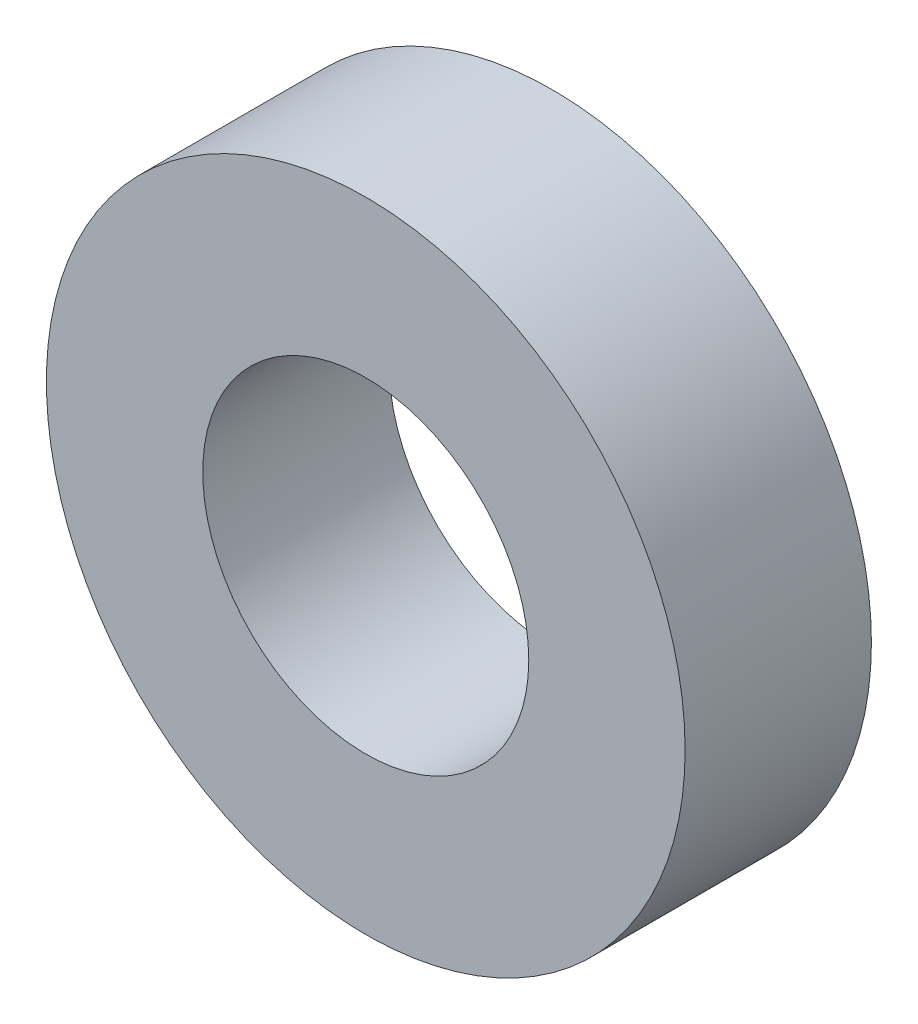
SolidWorks part; units mm, degrees
ref_plane "Front Plane" through (0, 0, 0) normal (0, 0, 1) x (1, 0, 0)
ref_plane "Top Plane" through (0, 0, 0) normal (0, 1, 0) x (1, 0, 0)
ref_plane "Right Plane" through (0, 0, 0) normal (1, 0, 0) x (0, 0, -1)
sketch "Sketch1" plane through (0, 0, 0) normal (0, 0, 1) x (1, 0, 0)
  circle A0 centre (0, 0) radius 6.125
  circle A1 centre (0, 0) radius 12
  dimension "D1" = 12.25
  dimension "D2" = 24
extrude "Boss-Extrude1" add sketch "Sketch1" along normal blind 7
equation "\"shaftDiameter\"= 12mm"
equation "\"outerDiameter\"= \"shaftDiameter\" + 12mm"
equation "\"D1@Sketch1\"=\"shaftDiameter\"+0.25"
equation "\"D2@Sketch1\"=\"outerDiameter\""
equation "\"bearingDepth\"= 7mm"
equation "\"D1@Boss-Extrude1\"=\"bearingDepth\""
